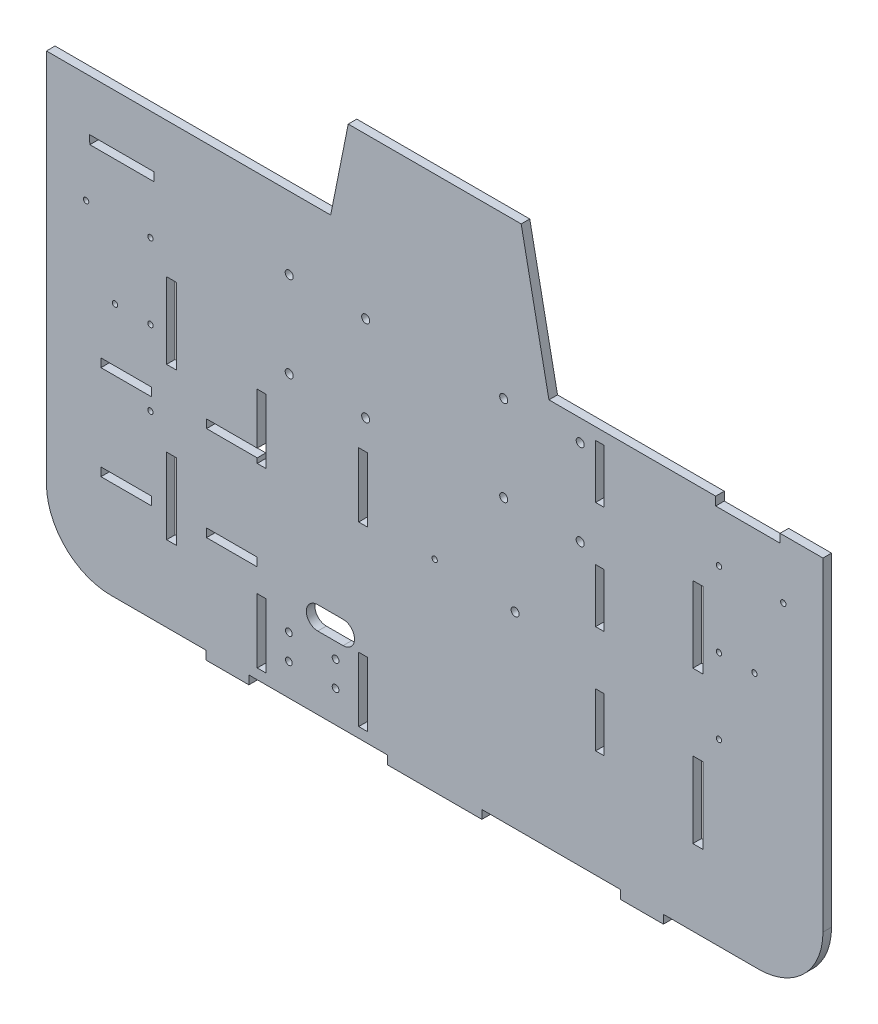
SolidWorks part; units mm, degrees
material "Gillfab4009"
ref_plane "Front Plane" through (0, 0, 0) normal (0, 0, 1) x (1, 0, 0)
ref_plane "Top Plane" through (0, 0, 0) normal (0, 1, 0) x (1, 0, 0)
ref_plane "Right Plane" through (0, 0, 0) normal (1, 0, 0) x (0, 0, -1)
sketch "Sketch2" plane through (0, 0, 0) normal (0, 0, 1) x (1, 0, 0)
  line L0 (-408.9218, 152.7574) -> (-459.7218, 152.7574)
  line L1 (332.7218, 152.7574) -> (135.2505, 152.7574)
  line L2 (-135.2505, 152.7574) -> (-332.1008, 152.7574)
  line L3 (-102.3945, 316.7286) -> (-135.2505, 152.7574)
  line L4 (102.3945, 316.7286) -> (-102.3945, 316.7286)
  line L6 (-459.7218, 152.7574) -> (-459.7218, -230.7826)
  line L7 (459.7218, 152.7574) -> (408.9218, 152.7574)
  line L8 (-303.52, -306.9826) -> (-383.5218, -306.9826)
  line L9 (-270.8, -317.1426) -> (-220, -317.1426)
  line L11 (408.9218, 142.6164) -> (408.9218, 152.7574)
  line L12 (332.7218, 142.6164) -> (408.9218, 142.6164)
  line L13 (332.7218, 152.7574) -> (332.7218, 142.6164)
  line L14 (-408.3008, 142.6164) -> (-332.1008, 142.6164)
  line L15 (-408.9218, 152.7574) -> (-408.3008, 142.6164)
  line L16 (-332.1008, 142.6164) -> (-332.1008, 152.7574)
  line L17 (305.6323, -37.2346) -> (317.4824, -37.2346)
  line L18 (305.6323, 52.6814) -> (305.6323, -37.2346)
  line L19 (317.4824, 52.6814) -> (305.6323, 52.6814)
  line L20 (317.4824, -37.2346) -> (317.4824, 52.6814)
  line L21 (305.6323, -217.0666) -> (317.4824, -217.0666)
  line L22 (317.4824, -217.0666) -> (317.4824, -127.1506)
  line L23 (317.4824, -127.1506) -> (305.6323, -127.1506)
  line L24 (305.6323, -127.1506) -> (305.6323, -217.0666)
  line L25 (252, -307.3966) -> (202.6964, -307.3966) construction
  line L27 (0, 316.7286) -> (0, 0) construction
  line L28 (0, 0) -> (0, -307.6709) construction
  line L39 (303.52, -306.9826) -> (383.5218, -306.9826)
  line L44 (-190.5, 75.1277) -> (-190.5, 11.4601) construction
  line L45 (-190.5, -52.225) -> (-190.5, -115.91) construction
  line L46 (-190.5, -179.5951) -> (-190.5, -243.2802) construction
  line L47 (190.5, 75.1277) -> (190.5, 14.3511) construction
  line L48 (190.5, -307.3966) -> (190.5, -243.6941) construction
  line L49 (190.5, 14.3511) -> (190.5, -115.91) construction
  line L52 (190.5, -115.91) -> (190.5, -243.6941) construction
  line L53 (459.7218, 152.7574) -> (459.7218, 465.1616) construction
  line L55 (-335.16, -69.447) -> (-335.16, -79.447)
  line L56 (459.7218, 152.7574) -> (459.7218, -230.7826)
  line L57 (-270.16, -79.447) -> (-210.16, -79.447)
  line L58 (-270.16, -79.447) -> (-270.16, -69.447)
  line L59 (-335.16, -69.447) -> (-395.16, -69.447)
  line L60 (-395.16, -79.447) -> (-210.16, -79.447)
  line L61 (-210.16, -79.447) -> (-210.16, -69.447)
  line L62 (102.3945, 316.7286) -> (135.2505, 152.7574)
  line L63 (-210.16, -69.447) -> (-395.16, -69.447)
  line L64 (-395.16, -69.447) -> (-395.16, -79.447)
  line L65 (-395.16, -79.447) -> (-335.16, -79.447)
  line L67 (-210.16, -69.447) -> (-270.16, -69.447)
  line L68 (-395.16, -69.447) -> (-395.16, -79.447)
  line L69 (-210.16, -191.2542) -> (-395.16, -191.2542) construction
  line L70 (0, -307.6709) -> (0, -629.2246) construction
  line L71 (-210.16, -181.2542) -> (-395.16, -181.2542) construction
  line L72 (-335.16, -191.2542) -> (-335.16, -181.2542) construction
  line L73 (-270.16, -191.2542) -> (-270.16, -181.2542) construction
  line L75 (202.6964, -243.6941) -> (190.5, -243.6941) construction
  line L76 (202.6964, -243.6941) -> (202.6964, -307.3966) construction
  line L79 (200.66, -179.5951) -> (190.5, -179.5951)
  line L80 (190.5, -179.5951) -> (190.5, -115.91)
  line L81 (200.66, -115.91) -> (190.5, -115.91)
  line L82 (200.66, -115.91) -> (200.66, -179.5951)
  line L83 (190.5, -52.225) -> (190.5, 11.4601)
  line L84 (200.66, 11.4601) -> (190.5, 11.4601)
  line L85 (200.66, 11.4601) -> (200.66, -52.225)
  line L86 (200.66, -52.225) -> (190.5, -52.225)
  line L87 (200.66, 138.8128) -> (190.5, 138.8128)
  line L88 (190.5, 75.1277) -> (190.5, 138.8128)
  line L89 (200.66, 75.1277) -> (190.5, 75.1277)
  line L90 (200.66, 138.8128) -> (200.66, 75.1277)
  line L103 (-210.16, -191.4142) -> (-210.16, -294.8827) construction
  line L105 (-210.16, -191.2542) -> (-210.16, -181.2542) construction
  line L106 (-210.16, -79.447) -> (-210.16, -181.2542) construction
  line L107 (-200, -191.4142) -> (-200, -294.8827) construction
  line L108 (-200, -294.8827) -> (-210.16, -294.8827) construction
  line L109 (-200, -218.6827) -> (-210.16, -218.6827) construction
  line L110 (-200, -85.1624) -> (-210.16, -85.1624) construction
  line L111 (-200, -85.1624) -> (-210.16, -85.1624)
  line L112 (-200, -218.6827) -> (-210.16, -218.6827)
  line L113 (-200, -294.8827) -> (-210.16, -294.8827)
  line L114 (-200, -218.6827) -> (-200, -294.8827)
  line L115 (-210.16, -79.447) -> (-210.16, -85.1624)
  line L116 (-210.16, -191.2542) -> (-210.16, -181.2542)
  line L117 (-210.16, -218.6827) -> (-210.16, -294.8827)
  line L118 (-270.16, -191.2542) -> (-270.16, -181.2542)
  line L119 (-335.16, -191.2542) -> (-335.16, -181.2542)
  line L120 (-210.16, -181.2542) -> (-270.16, -181.2542)
  line L121 (-210.16, -191.2542) -> (-270.16, -191.2542)
  line L122 (-395.16, -181.2542) -> (-395.16, -191.2542)
  line L123 (-335.16, -191.2542) -> (-395.16, -191.2542)
  line L124 (-335.16, -181.2542) -> (-395.16, -181.2542)
  line L125 (-210.16, -69.447) -> (-210.16, -8.9624)
  line L126 (-210.16, -8.9624) -> (-200, -8.9624)
  line L127 (-200, -8.9624) -> (-200, -85.1624)
  line L128 (305.6323, -37.2346) -> (305.6323, -217.0666) construction
  line L129 (317.4824, -37.2346) -> (317.4824, -217.0666) construction
  line L130 (-305.6323, -217.0666) -> (-317.4824, -217.0666)
  line L131 (-305.6323, -127.1506) -> (-305.6323, -217.0666)
  line L132 (-90, -218.6827) -> (-90, -294.8827)
  line L133 (-79.84, -218.6827) -> (-90, -218.6827)
  line L134 (-79.84, -294.8827) -> (-79.84, -218.6827)
  line L135 (-90, -294.8827) -> (-79.84, -294.8827)
  line L136 (-90, -218.6827) -> (-90, -294.8827)
  line L137 (-79.84, -218.6827) -> (-90, -218.6827)
  line L138 (-79.84, -294.8827) -> (-79.84, -218.6827)
  line L139 (-90, -294.8827) -> (-79.84, -294.8827)
  line L140 (-90, -8.9624) -> (-90, -85.1624)
  line L141 (-79.84, -8.9624) -> (-90, -8.9624)
  line L142 (-79.84, -85.1624) -> (-79.84, -8.9624)
  line L143 (-90, -85.1624) -> (-79.84, -85.1624)
  line L144 (-90, -8.9624) -> (-90, -85.1624)
  line L145 (-79.84, -8.9624) -> (-90, -8.9624)
  line L146 (-79.84, -85.1624) -> (-79.84, -8.9624)
  line L147 (-90, -85.1624) -> (-79.84, -85.1624)
  line L148 (-317.4824, -127.1506) -> (-305.6323, -127.1506)
  line L149 (-317.4824, -217.0666) -> (-317.4824, -127.1506)
  line L150 (-305.6323, -37.2346) -> (-317.4824, -37.2346)
  line L151 (-317.4824, -37.2346) -> (-317.4824, 52.6814)
  line L152 (-317.4824, 52.6814) -> (-305.6323, 52.6814)
  line L153 (-305.6323, 52.6814) -> (-305.6323, -37.2346)
  line L154 (-183, -317.1426) -> (-183, -226.646) construction
  line L155 (-183, -304.4426) -> (-107.07, -304.4426) construction
  line L156 (-108.5, -207.6709) -> (-138.5, -207.6709) construction
  line L157 (-108.5, -221.1709) -> (-138.5, -221.1709)
  line L158 (-108.5, -194.1709) -> (-138.5, -194.1709)
  line L159 (-90, -191.4142) -> (-90, -294.8827) construction
  line L160 (-145.035, -304.4426) -> (-145.035, -269.4426) construction
  line L161 (-172.69, -269.4426) -> (-117.38, -269.4426) construction
  line L162 (-145.035, -239.4426) -> (-145.035, -269.4426) construction
  line L163 (-172.69, -239.4426) -> (-117.38, -239.4426) construction
  line L166 (-55.8292, -306.9826) -> (-55.8292, -317.1426) construction
  line L167 (55.8292, -306.9826) -> (55.8292, -317.1426) construction
  line L168 (-55.8292, -306.9826) -> (-55.8292, -317.1426)
  line L169 (55.8292, -306.9826) -> (55.8292, -317.1426)
  line L170 (303.52, -306.9826) -> (252, -306.9826) construction
  line L171 (-303.52, -306.9826) -> (-252, -306.9826) construction
  line L174 (-303.52, -306.9826) -> (-270.8, -306.9826)
  line L175 (303.52, -306.9826) -> (270.8, -306.9826)
  line L178 (220, -317.1426) -> (270.8, -317.1426)
  line L179 (-270.8, -306.9826) -> (-270.8, -317.1426) construction
  line L180 (-270.8, -306.9826) -> (-270.8, -317.1426)
  line L181 (-220, -306.9826) -> (-220, -317.1426) construction
  line L182 (-220, -306.9826) -> (-220, -317.1426)
  line L183 (220, -306.9826) -> (220, -317.1426) construction
  line L184 (270.8, -306.9826) -> (270.8, -317.1426) construction
  line L185 (220, -306.9826) -> (220, -317.1426)
  line L186 (270.8, -306.9826) -> (270.8, -317.1426)
  line L187 (-55.8292, -317.1426) -> (55.8292, -317.1426) construction
  line L188 (-55.8292, -317.1426) -> (55.8292, -317.1426)
  line L189 (55.8292, -306.9826) -> (220, -306.9826)
  line L190 (-220, -306.9826) -> (-55.8292, -306.9826)
  arc A0 (-383.5218, -306.9826) -> (-459.7218, -230.7826) centre (-383.5218, -230.7826) cw
  arc A2 (383.5218, -306.9826) -> (459.7218, -230.7826) centre (383.5218, -230.7826) ccw
  circle A6 centre (336.5503, -94.6874) radius 3.175
  circle A7 centre (378.5738, -5.7874) radius 3.175
  circle A8 centre (336.5503, -5.7874) radius 3.175
  circle A9 centre (336.5503, 83.1126) radius 3.175
  circle A10 centre (412.7503, 83.1126) radius 3.175
  circle A11 centre (-412.7503, 83.1126) radius 3.175
  circle A12 centre (-336.5503, 83.1126) radius 3.175
  circle A13 centre (-336.5503, -5.7874) radius 3.175
  circle A14 centre (-378.5738, -5.7874) radius 3.175
  circle A15 centre (-336.5503, -94.6874) radius 3.175
  circle A18 centre (172.2755, 127.3574) radius 4.7625
  circle A19 centre (172.2755, 25.7574) radius 4.7625
  circle A20 centre (81.7245, 25.7574) radius 4.7625
  circle A21 centre (81.7245, 127.3574) radius 4.7625
  circle A22 centre (-81.7245, 25.7574) radius 4.7625
  circle A23 centre (-81.7245, 127.3574) radius 4.7625
  circle A24 centre (-172.2755, 127.3574) radius 4.7625
  circle A25 centre (-172.2755, 25.7574) radius 4.7625
  circle A26 centre (0, -78.3826) radius 3.175
  circle A28 centre (95.25, -84.7326) radius 4.7625
  arc A29 (-108.5, -221.1709) -> (-108.5, -194.1709) centre (-108.5, -207.6709) ccw
  arc A30 (-138.5, -194.1709) -> (-138.5, -221.1709) centre (-138.5, -207.6709) ccw
  circle A31 centre (-172.69, -239.4426) radius 4
  circle A32 centre (-117.38, -239.4426) radius 4
  circle A33 centre (-117.38, -269.4426) radius 4
  circle A34 centre (-172.69, -269.4426) radius 4
  point P59 (-123.5, -207.6709)
  point P74 (-145.035, -269.4426)
  point P128 (-95, -207.6709)
  point P173 (-145.035, -239.4426)
  dimension "D1" = 76.2
  dimension "D8" = 76.2
  dimension "D21" = 27
  dimension "D22" = 30
  dimension "D33" = 8
  dimension "D3" = 919.4436
  dimension "D4" = 305.6323
  dimension "D5" = 183
  dimension "D6" = 12.7
  dimension "D7" = 152.7574
  dimension "D9" = 75.93
  dimension "D11" = 35
  dimension "D12" = 10.16
  dimension "D13" = 190.5
  dimension "D14" = 190.5
  dimension "D15" = 50.8
  dimension "D16" = 0
  dimension "D17" = 50.8
  dimension "D18" = 76.2
  dimension "D19" = 0
  dimension "D23" = 5
  dimension "D24" = 55.31
  dimension "D25" = 11.8501
  dimension "D26" = 52.6814
  dimension "D27" = 89.916
  dimension "D28" = 89.916
  dimension "D29" = 89.916
  dimension "D30" = 316.7286
  dimension "D31" = 55.31
  dimension "D32" = 30
  dimension "D20" = 0
extrude "Boss-Extrude1" add sketch "Sketch2" against normal blind 10.16
sketch "Sketch3" plane through (0, 0, 0) normal (0, 0, 1) x (1, 0, 0)
  line L0 (250, -275.561) -> (419.7218, -275.561) construction
  line L1 (419.7218, -275.561) -> (419.7218, 24.439) construction
  line L2 (419.7218, 24.439) -> (250, 24.439) construction
  line L3 (459.7218, -230.7826) -> (459.7218, 152.7574) construction
  line L4 (-545.9218, 194.0186) -> (545.9218, 194.0186) construction
  line L5 (-545.9218, 213.0186) -> (545.9218, 213.0186) construction
  dimension "D1" = 40
  dimension "D2" = 19
sketch "Sketch4" plane through (0, 152.7574, 0) normal (0, 1, 0) x (1, 0, 0)
  line L0 (-102.3945, 0) -> (-135.2505, 0) construction
  line L1 (-459.7218, 10.16) -> (-108.0462, 10.16)
  line L2 (-459.7218, 10.16) -> (-459.7218, 0)
  line L3 (-459.7218, 0) -> (-108.0462, 0)
  line L4 (-108.0462, 10.16) -> (-108.0462, 0)
extrude "Boss-Extrude2" add sketch "Sketch4" along normal up to vertex (60.2612 mm away) up to point (-545.9218, 213.0186, 0)
